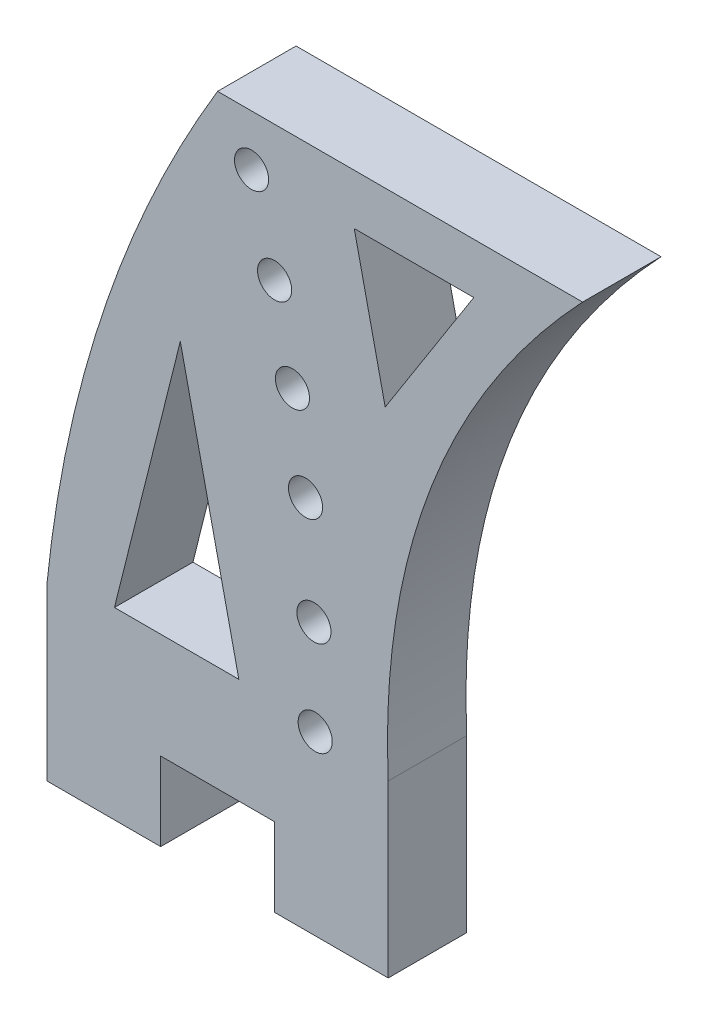
SolidWorks part; units mm, degrees
ref_plane "Front Plane" through (0, 0, 0) normal (0, 0, 1) x (1, 0, 0)
ref_plane "Top Plane" through (0, 0, 0) normal (0, 1, 0) x (1, 0, 0)
ref_plane "Right Plane" through (0, 0, 0) normal (1, 0, 0) x (0, 0, -1)
sketch "Sketch3" plane through (0, 0, 0) normal (0, 0, 1) x (1, 0, 0)
  line L1 (12.7, -6.35) -> (-12.7, -6.35)
  line L2 (12.7, -6.35) -> (12.7, 6.35)
  line L3 (12.7, 6.35) -> (-12.7, 6.35)
  line L4 (-12.7, -6.35) -> (-12.7, 6.35)
  line L5 (12.7, -6.35) -> (-12.7, 6.35) construction
  line L6 (12.7, 6.35) -> (-12.7, -6.35) construction
  point P0 (0, 0)
  dimension "D1" = 12.7
  dimension "D2" = 25.4
extrude "Boss-Extrude2" add sketch "Sketch3" along normal blind 5.842
sketch "Sketch4" plane through (0, 0, 5.842) normal (0, 0, 1) x (1, 0, 0)
  line L0 (-12.7, -0.508) -> (12.7, -0.508) construction
  line L1 (-12.7, 6.35) -> (-12.7, -6.35) construction
  line L2 (12.7, -6.35) -> (12.7, 6.35) construction
  line L3 (-12.7, -6.35) -> (12.7, -6.35) construction
  line L4 (-12.7, -6.35) -> (-4.2333, -6.35) construction
  line L5 (4.2333, -6.35) -> (12.7, -6.35) construction
  line L6 (-4.2333, -6.35) -> (4.2333, -6.35)
  line L7 (-4.2333, -6.35) -> (-4.2333, -0.508)
  line L8 (-4.2333, -0.508) -> (4.2333, -0.508)
  line L9 (4.2333, -6.35) -> (4.2333, -0.508)
  dimension "D1" = 5.842
extrude "Cut-Extrude1" cut sketch "Sketch4" against normal through all
sketch "Sketch5" plane through (0, 0, 5.842) normal (0, 0, 1) x (1, 0, 0)
  line L0 (0, 44.45) -> (27.1644, 44.45)
  line L1 (4.2333, -6.35) -> (12.7, -6.35) construction
  line L2 (12.7, 6.35) -> (-12.7, 6.35)
  spline S0 degree 2 poles (-12.7, 6.35) (-10.6198, 26.7579) (0, 44.45) knots 0 0 0 1 1 1
  spline S1 degree 2 poles (12.7, 6.35) (11.7488, 28.1019) (27.1644, 44.45) knots 0 0 0 1 1 1
  dimension "D1" = 50.8
extrude "Boss-Extrude3" add sketch "Sketch5" against normal blind 5.842
sketch "Sketch10" plane through (0, 0, 5.842) normal (0, 0, 1) x (1, 0, 0)
  circle A1 centre (7.2642, 6.8005) radius 1.27
extrude "Cut-Extrude8" cut sketch "Sketch10" against normal blind 7.62
sketch "Sketch12" plane through (0, 0, 5.842) normal (0, 0, 1) x (1, 0, 0)
  circle A2 centre (5.5726, 28.0913) radius 1.27
  circle A3 centre (6.5463, 21.5324) radius 1.27
  circle A4 centre (7.1733, 13.822) radius 1.27
  circle A5 centre (2.5292, 40.6593) radius 1.27
  circle A6 centre (7.2642, 6.8005) radius 1.27 construction
  circle A8 centre (4.2439, 34.3977) radius 1.27
  dimension "D2" = 2.54
extrude "Cut-Extrude9" cut sketch "Sketch12" against normal blind 7.62
sketch "Sketch13" plane through (0, 0, 5.842) normal (0, 0, 1) x (1, 0, 0)
  line L0 (-2.7741, 26.9461) -> (-7.6751, 7.3419)
  line L1 (-7.6751, 7.3419) -> (1.5824, 7.3419)
  line L2 (1.5824, 7.3419) -> (-2.7741, 26.9461)
  line L3 (10.1728, 40.693) -> (12.4747, 30.3347)
  line L4 (12.4747, 30.3347) -> (19.0663, 40.693)
  line L5 (19.0663, 40.693) -> (10.1728, 40.693)
extrude "Cut-Extrude10" cut sketch "Sketch13" against normal blind 7.62
